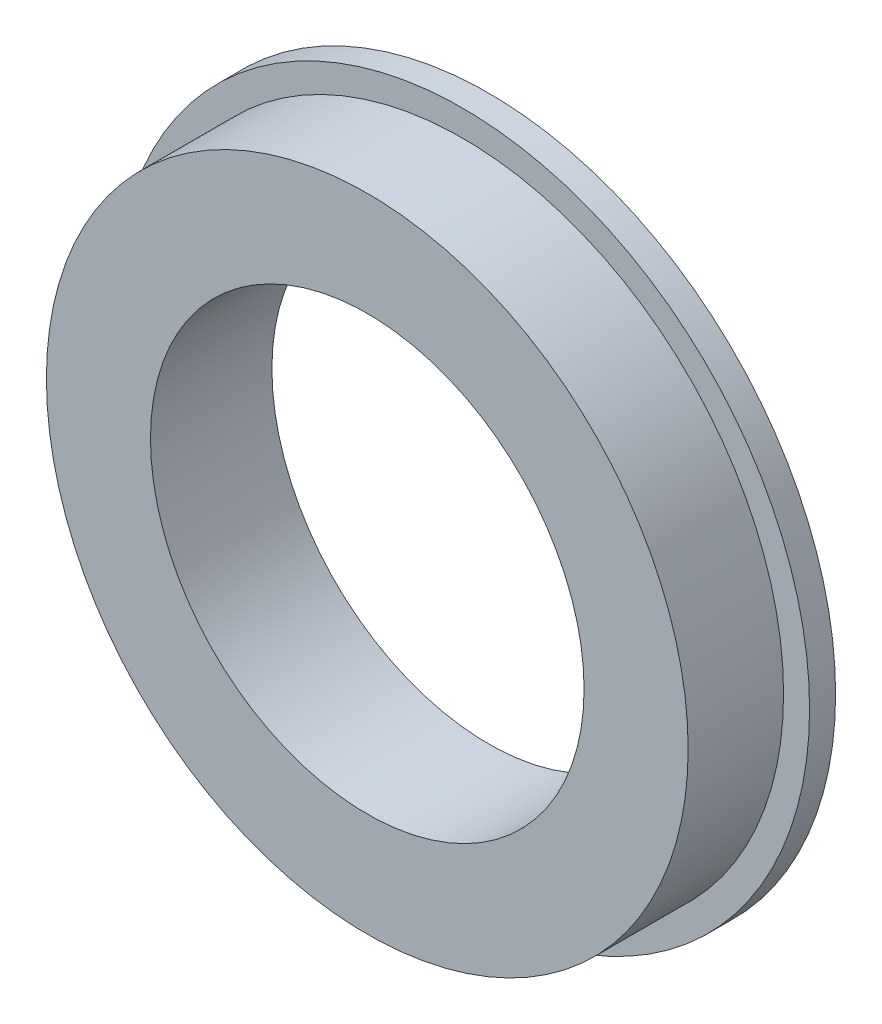
SolidWorks part; units mm, degrees
material "1.7030 (28Cr4)"
ref_plane "前视基准面" through (0, 0, 0) normal (0, 0, 1) x (1, 0, 0)
ref_plane "上视基准面" through (0, 0, 0) normal (0, 1, 0) x (1, 0, 0)
ref_plane "右视基准面" through (0, 0, 0) normal (1, 0, 0) x (0, 0, -1)
sketch "Sketch1" plane through (0, 0, 0) normal (0, 0, 1) x (1, 0, 0)
  circle A0 centre (0, 0) radius 20
  circle A1 centre (0, 0) radius 12.5
  dimension "D1" = 40
  dimension "D2" = 25
extrude "Extrude1" add sketch "Sketch1" along normal blind 1.5
sketch "Sketch2" plane through (0, 0, 1.5) normal (0, 0, 1) x (1, 0, 0)
  circle A0 centre (0, 0) radius 18.5
  circle A1 centre (0, 0) radius 12.5
  dimension "D1" = 37
  dimension "D2" = 25
extrude "Extrude2" add sketch "Sketch2" along normal blind 5.5
